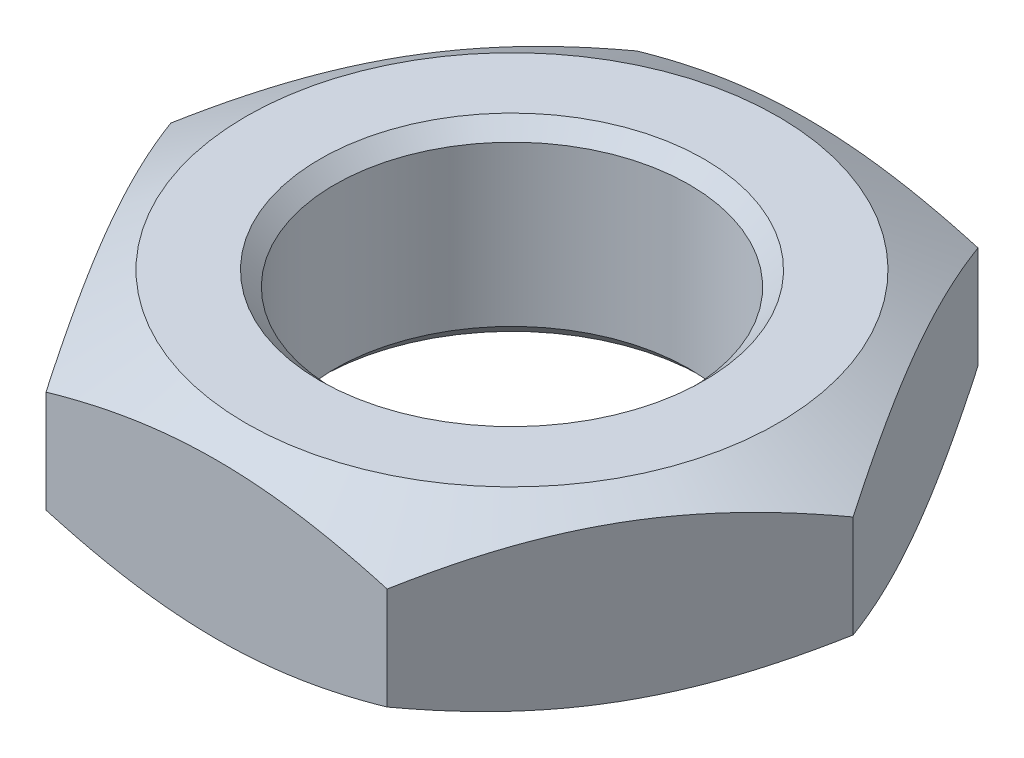
SolidWorks part; units mm, degrees
ref_plane "Спереди" through (0, 0, 0) normal (0, 0, 1) x (1, 0, 0)
ref_plane "Сверху" through (0, 0, 0) normal (0, 1, 0) x (1, 0, 0)
ref_plane "Справа" through (0, 0, 0) normal (1, 0, 0) x (0, 0, -1)
sketch "Эскиз1" plane through (0, 0, 0) normal (0, 1, 0) x (1, 0, 0)
  line L0 (0, -12.4837) -> (0, 13.3994) construction
  line L1 (-14.932, 0) -> (13.7558, 0) construction
  line L2 (-2.8868, 5) -> (2.8868, 5)
  line L3 (2.8868, 5) -> (5.7735, 0)
  line L4 (5.7735, 0) -> (2.8868, -5)
  line L5 (2.8868, -5) -> (-2.8868, -5)
  line L6 (-2.8868, -5) -> (-5.7735, 0)
  line L7 (-5.7735, 0) -> (-2.8868, 5)
  dimension "D1" = 5
  dimension "D2" = 120
  dimension "D3" = 120
  dimension "D4" = 10
  dimension "D5" = 120
  dimension "D6" = 10
  dimension "D7" = 5
extrude "Вытянуть1" add sketch "Эскиз1" along normal blind 3.2
sketch "Эскиз2" plane through (0, 3.2, 0) normal (0, 1, 0) x (-1, 0, 0)
  circle A0 centre (0, 0) radius 3
  dimension "D1" = 6
extrude "Вырез-Вытянуть1" cut sketch "Эскиз2" against normal blind 5
ref_axis "Ось1" through (0, 3.2, 0) along (0, -1, 0)
sketch "Эскиз3" plane through (0, 0, 0) normal (0, 0, 1) x (1, 0, 0)
  line L0 (-4.5, 5.3198) -> (-4.5, -0.4639) construction
  line L3 (-4.5, 3.2) -> (-6.5, 2.0453)
  line L4 (-2.8868, 3.2) -> (-5.7735, 3.2) construction
  line L6 (-6.5, 2.0453) -> (-6.5, 3.2)
  line L7 (-6.5, 3.2) -> (-4.5, 3.2)
  line L8 (-4.5, 0) -> (-6.5, 1.1547)
  line L9 (-2.8868, 0) -> (-5.7735, 0) construction
  line L10 (-6.5, 1.1547) -> (-6.5, 0)
  line L11 (-6.5, 0) -> (-4.5, 0)
  line L12 (-4.5, 0) -> (-4.4961, 0.0114)
  dimension "D1" = 4.5
  dimension "D2" = 30
  dimension "D3" = 2
  dimension "D4" = 2
  dimension "D5" = 30
revolve "Вырез-Повернуть1" cut sketch "Эскиз3" angle 360 about axis through (0, 3.2, 0) along (0, -1, 0)
chamfer "Фаска1" distance 0.25 angle 45 2 edges at (0, 3.2, 3) (0, 0, -3)
